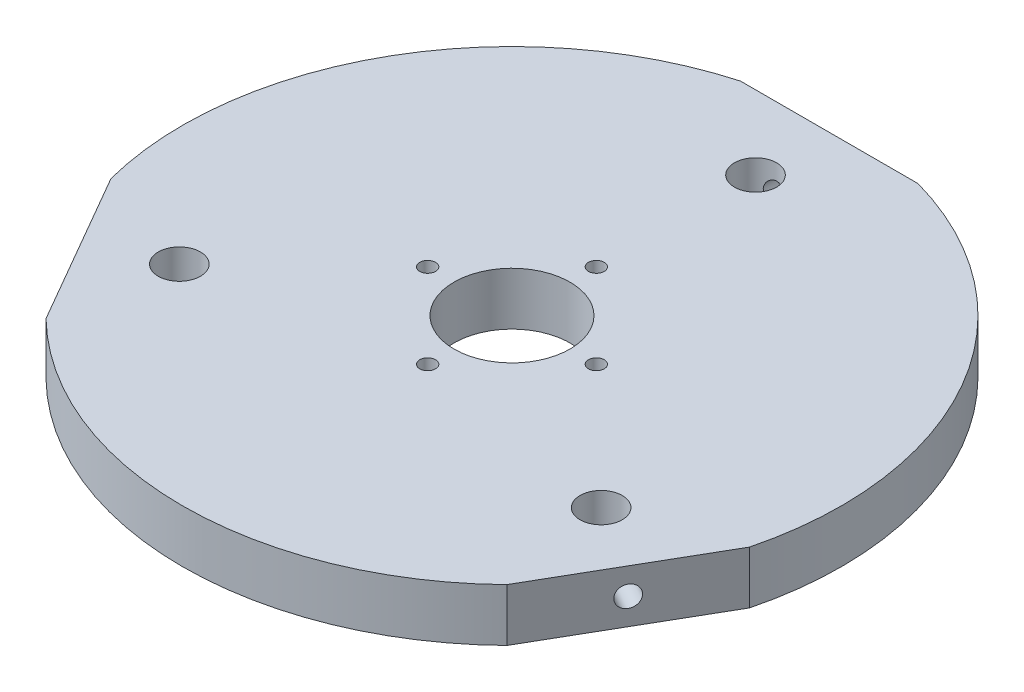
SolidWorks part; units mm, degrees
material "1060 Alloy"
ref_plane "Front Plane" through (0, 0, 0) normal (0, 0, 1) x (1, 0, 0)
ref_plane "Top Plane" through (0, 0, 0) normal (0, 1, 0) x (1, 0, 0)
ref_plane "Right Plane" through (0, 0, 0) normal (1, 0, 0) x (0, 0, -1)
sketch "Sketch1" plane through (0, 0, 0) normal (0, 1, 0) x (1, 0, 0)
  line L0 (-40, -23.094) -> (40, -23.094) construction
  line L1 (40, -23.094) -> (0, 46.188) construction
  line L2 (0, 46.188) -> (-40, -23.094) construction
  line L3 (-40, -23.094) -> (-54.1266, -31.25) construction
  circle A0 centre (0, 46.188) radius 4
  circle A1 centre (40, -23.094) radius 4
  circle A2 centre (-40, -23.094) radius 4
  circle A3 centre (0, 0) radius 62.5
  dimension "D4" = 8
  dimension "D5" = 8
  dimension "D6" = 8
  dimension "D7" = 125
  dimension "D1" = 80
  dimension "D2" = 80
  dimension "D3" = 80
extrude "Boss-Extrude1" add sketch "Sketch1" along normal blind 10
sketch "Sketch2" plane through (0, 10, 0) normal (0, 1, 0) x (1, 0, 0)
  line L0 (0, 0) -> (-40, -23.094) construction
  line L1 (-40, -23.094) -> (-67.1185, -38.7509) construction
  line L2 (0, 0) -> (40, -23.094) construction
  line L3 (40, -23.094) -> (73.8523, -42.6387) construction
  line L4 (0, 0) -> (0, 46.188) construction
  line L5 (0, 46.188) -> (0, 68.5159) construction
  line L6 (-68.6615, -1.4509) -> (-25.024, -77.0333) construction
  line L7 (63.3211, -10.7007) -> (40.6097, -50.0381) construction
  line L8 (-14.2926, 60.188) -> (16.8158, 60.188) construction
  line L9 (-39.5818, -51.8183) -> (-64.7131, -8.2897)
  line L10 (-39.5818, -51.8183) -> (-52.5562, -59.309)
  line L11 (-64.7131, -8.2897) -> (-77.6875, -15.7805)
  line L12 (-52.5562, -59.309) -> (-77.6875, -15.7805)
  line L13 (40.6097, -50.0381) -> (63.3211, -10.7007)
  line L14 (40.6097, -50.0381) -> (52.9299, -57.1511)
  line L15 (63.3211, -10.7007) -> (75.6413, -17.8138)
  line L16 (52.9299, -57.1511) -> (75.6413, -17.8138)
  line L17 (-21.515, 60.188) -> (22.4572, 60.188)
  line L18 (-21.515, 60.188) -> (-21.515, 68.9)
  line L19 (22.4572, 60.188) -> (22.4572, 68.9)
  line L20 (-21.515, 68.9) -> (22.4572, 68.9)
  point P13 (-52.1244, -30.094)
  point P16 (52.1244, -30.094)
  point P19 (0, 60.188)
  dimension "D2" = 14
  dimension "D3" = 14
  dimension "D4" = 14
extrude "Cut-Extrude1" cut sketch "Sketch2" against normal blind 10
sketch "Sketch3" plane through (52.1244, 0, 30.094) normal (0.866, 0, 0.5) x (0.5, 0, -0.866)
  line L0 (16.842, 10) -> (-16.842, 10) construction
  line L1 (-16.842, 0) -> (-16.842, 10) construction
  line L2 (16.842, 10) -> (16.842, 0) construction
  circle A0 centre (0.002, 5) radius 2
  point P9 (16.842, 5)
  dimension "D1" = 4
  dimension "D2" = 5
  dimension "D3" = 33.6839
  dimension "D4" = 16.84
extrude "Cut-Extrude2" cut sketch "Sketch3" against normal blind 12
sketch "Sketch4" plane through (-52.1244, 0, 30.094) normal (-0.866, 0, 0.5) x (0.5, 0, 0.866)
  line L0 (16.842, 10) -> (-16.842, 10) construction
  line L1 (-16.842, 0) -> (-16.842, 10) construction
  line L2 (16.842, 10) -> (16.842, 0) construction
  circle A0 centre (-0.002, 5) radius 2
  dimension "D1" = 4
  dimension "D2" = 5
  dimension "D3" = 16.84
  dimension "D4" = 33.6839
extrude "Cut-Extrude3" cut sketch "Sketch4" against normal blind 12
sketch "Sketch5" plane through (0, 0, -60.188) normal (0, 0, -1) x (-1, 0, 0)
  line L0 (16.842, 10) -> (-16.842, 10) construction
  line L1 (-16.842, 0) -> (-16.842, 10) construction
  line L2 (16.842, 10) -> (16.842, 0) construction
  circle A0 centre (-0.002, 5) radius 2
  dimension "D1" = 4
  dimension "D2" = 5
  dimension "D3" = 33.6839
  dimension "D4" = 16.84
extrude "Cut-Extrude4" cut sketch "Sketch5" against normal blind 12
sketch "Sketch6" plane through (0, 10, 0) normal (0, 1, 0) x (1, 0, 0)
  circle A0 centre (0, 0) radius 11
  dimension "D1" = 22
extrude "Cut-Extrude5" cut sketch "Sketch6" against normal blind 12
sketch "Sketch7" plane through (0, 10, 0) normal (0, 1, 0) x (1, 0, 0)
  circle A0 centre (-16, 0) radius 1.5
  circle A1 centre (0, 16) radius 1.5
  circle A2 centre (16, 0) radius 1.5
  circle A3 centre (0, -16) radius 1.5
  point P13 (0, 0)
  point P14 (0, 0)
  dimension "D1" = 3
  dimension "D2" = 4
extrude "Cut-Extrude6" cut sketch "Sketch7" against normal blind 10
